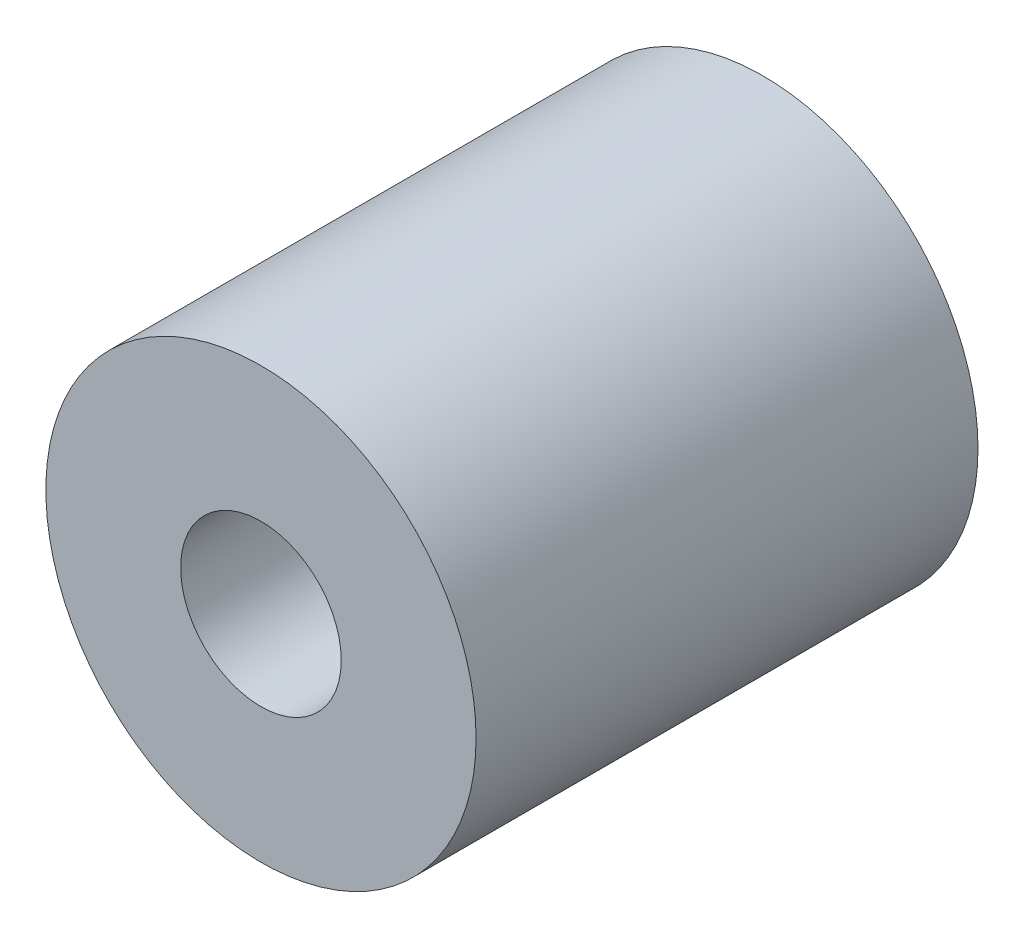
SolidWorks part; units mm, degrees
ref_plane "Front Plane" through (0, 0, 0) normal (0, 0, 1) x (1, 0, 0)
ref_plane "Top Plane" through (0, 0, 0) normal (0, 1, 0) x (1, 0, 0)
ref_plane "Right Plane" through (0, 0, 0) normal (1, 0, 0) x (0, 0, -1)
sketch "Sketch1" plane through (0, 0, 0) normal (0, 0, 1) x (1, 0, 0)
  circle A0 centre (0, 0) radius 4.7625
  circle A1 centre (0, 0) radius 1.778
  dimension "OD" = 9.525
  dimension "ID" = 3.556
extrude "Extrude1" add sketch "Sketch1" along normal mid plane 11.1125
sketch "Sketch2" plane through (0, 0, 0) normal (1, 0, 0) x (0, 0, -1)
  line L0 (-5.5562, -1.778) -> (5.5562, -1.778) construction
  line L3 (5.5562, 1.778) -> (-5.5562, 1.778) construction
  line L5 (-5.5562, -1.778) -> (5.5562, -1.778)
  line L6 (5.5562, 1.778) -> (-5.5562, 1.778)
sketch "Sketch4" plane through (0, 0, 5.5562) normal (0, 0, 1) x (1, 0, 0)
  line L0 (0, 0) -> (-1.2572, 1.2572)
  line L1 (0, -3.0559) -> (0, 3.0559) construction
  circle A0 centre (0, 0) radius 1.778 construction
  dimension "D1" = 45
